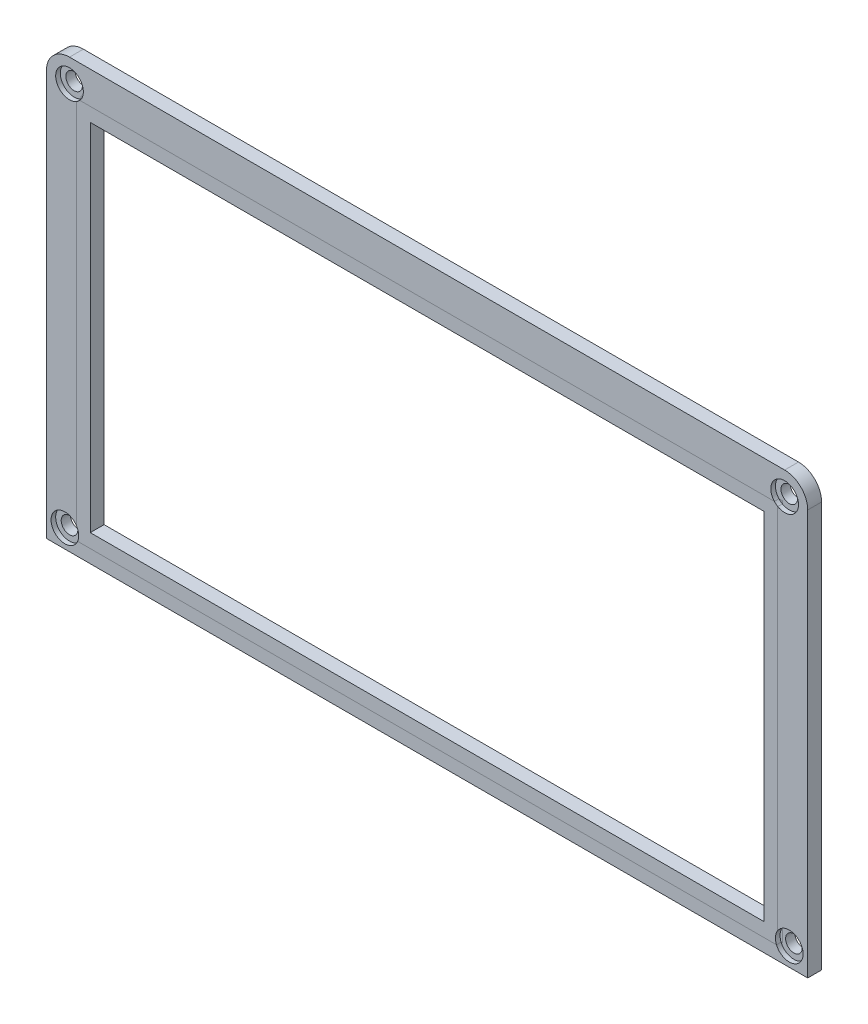
SolidWorks part; units mm, degrees
ref_plane "前视基准面" through (0, 0, 0) normal (0, 0, 1) x (1, 0, 0)
ref_plane "上视基准面" through (0, 0, 0) normal (0, 1, 0) x (1, 0, 0)
ref_plane "右视基准面" through (0, 0, 0) normal (1, 0, 0) x (0, 0, -1)
other "Configuration Table"
sketch "草图2" plane through (0, 0, 0) normal (0, 0, 1) x (1, 0, 0)
  line L6 (7.5707, 11.5756) -> (159.5707, 11.5756)
  line L7 (1.0707, 13.5756) -> (1.0707, -65.6217)
  line L8 (1.0707, -65.6217) -> (1.0707, -74.2722)
  line L9 (1.0707, -74.2722) -> (166.0707, -74.2722)
  line L10 (166.0707, -74.2722) -> (166.0707, -65.6217)
  line L11 (166.0707, -65.6217) -> (166.0707, 13.5756)
  line L12 (161.0707, 18.5756) -> (6.0707, 18.5756)
  line L13 (7.5707, -71.4244) -> (159.5707, -71.4244)
  line L14 (159.5707, 11.5756) -> (159.5707, -71.4244)
  line L15 (7.5707, 11.5756) -> (7.5707, -71.4244)
  arc A2 (166.0707, 13.5756) -> (161.0707, 18.5756) centre (161.0707, 13.5756) ccw
  arc A3 (6.0707, 18.5756) -> (1.0707, 13.5756) centre (6.0707, 13.5756) ccw
extrude "凸台-拉伸1" add sketch "草图2" along normal blind 3
sketch "草图3" plane through (0, 0, 3) normal (0, 0, 1) x (1, 0, 0)
  line L0 (7.5707, -71.4244) -> (159.5707, -71.4244) construction
  line L1 (159.5707, -71.4244) -> (159.5707, 11.5756) construction
  line L2 (159.5707, 11.5756) -> (7.5707, 11.5756) construction
  line L3 (7.5707, 11.5756) -> (7.5707, -71.4244) construction
  line L4 (1.0707, 13.5756) -> (1.0707, -74.2722)
  line L5 (1.0707, -74.2722) -> (166.0707, -74.2722)
  line L6 (166.0707, -74.2722) -> (166.0707, 13.5756)
  line L7 (161.0707, 18.5756) -> (6.0707, 18.5756)
  line L8 (1.0707, 13.5756) -> (1.0707, -74.2722)
  line L9 (1.0707, -74.2722) -> (166.0707, -74.2722)
  line L10 (166.0707, -74.2722) -> (166.0707, 13.5756)
  line L11 (161.0707, 18.5756) -> (6.0707, 18.5756)
  line L12 (7.5707, -71.4244) -> (159.5707, -71.4244)
  line L13 (159.5707, -71.4244) -> (159.5707, 11.5756)
  line L14 (159.5707, 11.5756) -> (7.5707, 11.5756)
  line L15 (7.5707, 11.5756) -> (7.5707, -71.4244)
  line L16 (10.5707, 8.5756) -> (10.5707, -68.4244)
  line L17 (10.5707, -68.4244) -> (156.5707, -68.4244)
  line L18 (156.5707, -68.4244) -> (156.5707, 8.5756)
  line L19 (156.5707, 8.5756) -> (10.5707, 8.5756)
  arc A2 (6.0707, 18.5756) -> (1.0707, 13.5756) centre (6.0707, 13.5756) ccw
  arc A3 (166.0707, 13.5756) -> (161.0707, 18.5756) centre (161.0707, 13.5756) ccw
  arc A4 (6.0707, 18.5756) -> (1.0707, 13.5756) centre (6.0707, 13.5756) ccw
  arc A5 (166.0707, 13.5756) -> (161.0707, 18.5756) centre (161.0707, 13.5756) ccw
  line M17 (159.5707, -71.4244) -> (7.5707, -71.4244)
  line M18 (7.5707, -71.4244) -> (7.5707, 11.5756)
  line M19 (7.5707, 11.5756) -> (159.5707, 11.5756)
  line M20 (159.5707, 11.5756) -> (159.5707, -71.4244)
  dimension "D1" = 0
  dimension "D2" = 3
extrude "凸台-拉伸2" add sketch "草图3" against normal blind 3 separate body contours L19 L18 L17 L16 M17 M20 M19 M18
sketch "草图4" plane through (0, 0, 3) normal (0, 0, 1) x (1, 0, 0)
  line L0 (1.0707, 13.5756) -> (1.0707, -74.2722) construction
  line L1 (1.0707, -74.2722) -> (166.0707, -74.2722) construction
  line L2 (83.5707, 18.5756) -> (83.5707, 50018.5756) construction
  line L3 (161.0707, 18.5756) -> (6.0707, 18.5756) construction
  circle A0 centre (6.0707, 13.5756) radius 1.8
  circle A1 centre (161.0707, 13.5756) radius 1.8
  circle A2 centre (5.0707, -70.2722) radius 1.8
  circle A3 centre (162.0707, -70.2722) radius 1.8
  point P16 (83.5707, 18.5756)
  dimension "D1" = 3.6
  dimension "D2" = 3.6
  dimension "D3" = 3.6
  dimension "D4" = 4
  dimension "D5" = 4
extrude "切除-拉伸1" cut sketch "草图4" against normal up to next (3 mm away)
sketch "草图5" plane through (0, 0, 3) normal (0, 0, 1) x (1, 0, 0)
  circle A0 centre (6.0707, 13.5756) radius 3
  circle A1 centre (161.0707, 13.5756) radius 3
  circle A3 centre (5.0707, -70.2722) radius 3
  circle A4 centre (162.0707, -70.2722) radius 3
  dimension "D1" = 6
  dimension "D2" = 6
extrude "切除-拉伸2" cut sketch "草图5" against normal blind 1
